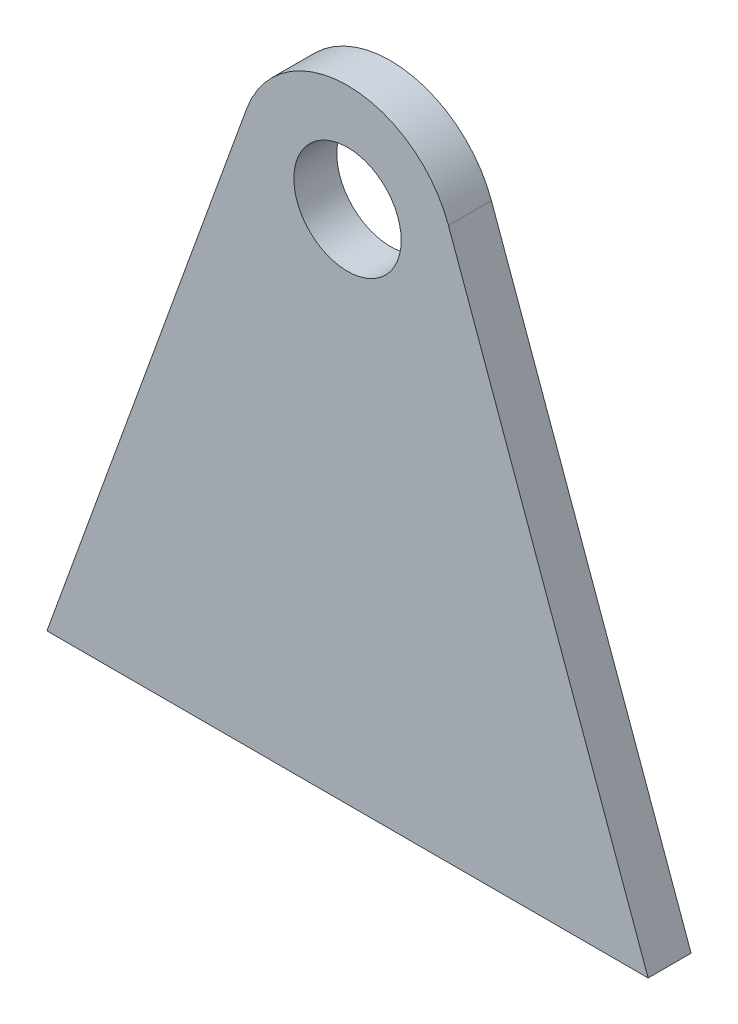
SolidWorks part; units mm, degrees
ref_plane "前基準面" through (0, 0, 0) normal (0, 0, 1) x (1, 0, 0)
ref_plane "上基準面" through (0, 0, 0) normal (0, 1, 0) x (1, 0, 0)
ref_plane "右基準面" through (0, 0, 0) normal (1, 0, 0) x (0, 0, -1)
ref_plane "平面1"
sketch "草圖1" plane through (0, 0, 0) normal (0, 0, 1) x (1, 0, 0)
  line L0 (0, 0) -> (140, 0)
  line L1 (140, 0) -> (47.0176, 257.0102)
  line L2 (-47.0176, 257.0102) -> (-140, 0)
  line L3 (-140, 0) -> (0, 0)
  arc A0 (47.0176, 257.0102) -> (-47.0176, 257.0102) centre (0, 240) ccw
  circle A1 centre (0, 240) radius 25
  dimension "D3" = 100
  dimension "D5" = 50
  dimension "D1" = 140
  dimension "D2" = 240
  dimension "D4" = 140
extrude "擠出1" add sketch "草圖1" against normal blind 20 contours L1 A0 L2 L3 L0 A1
